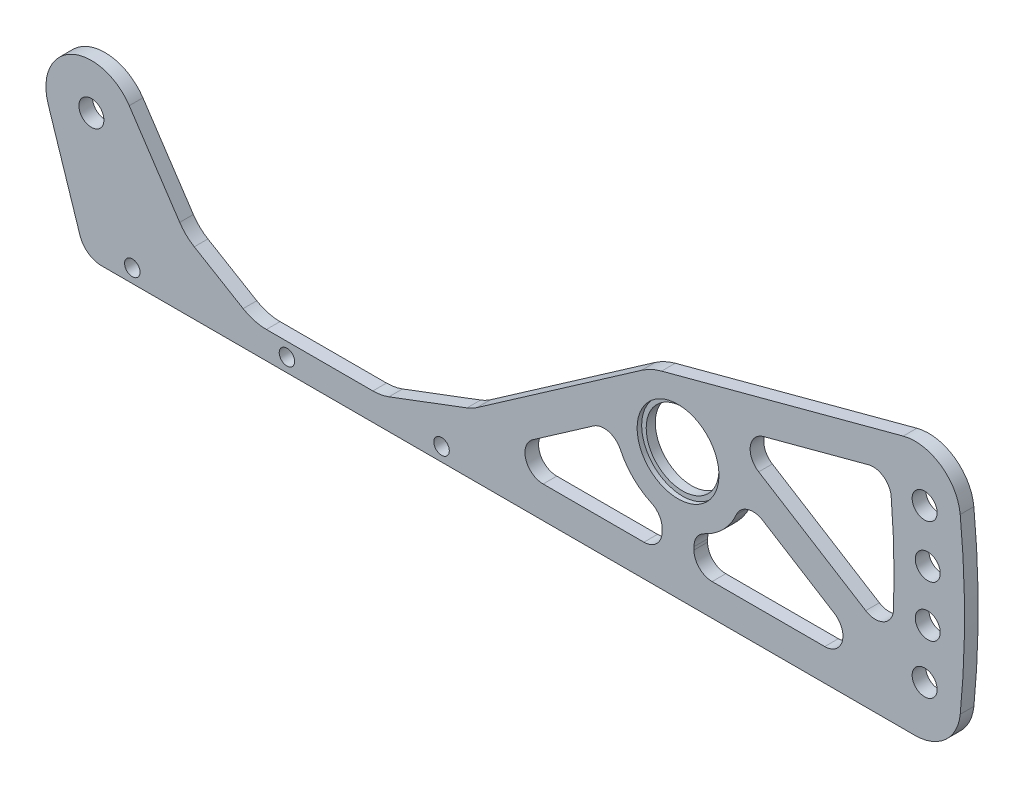
SolidWorks part; units mm, degrees
ref_plane "Спереди" through (0, 0, 0) normal (0, 0, 1) x (1, 0, 0)
ref_plane "Сверху" through (0, 0, 0) normal (0, 1, 0) x (1, 0, 0)
ref_plane "Справа" through (0, 0, 0) normal (1, 0, 0) x (0, 0, -1)
sketch "Эскиз1" plane through (0, 0, 0) normal (0, 0, 1) x (1, 0, 0)
  line L0 (-31.9542, -25) -> (253.1565, -25) construction
  line L1 (9, 35.6094) -> (9, -47.5785) construction
  line L2 (-39.2405, -28) -> (262.4545, -28) construction
  line L3 (-31.9542, -22) -> (262.4545, -22) construction
  line L4 (-9.5085, -3.0964) -> (-1.3987, -28)
  line L5 (8.3266, 5.5379) -> (20.6752, -13.0291)
  line L6 (-26.4187, 0) -> (187.6558, 0) construction
  line L7 (121.0002, 11.4893) -> (83.7656, -14.4365)
  line L8 (63.7181, -22) -> (35.7314, -22)
  line L9 (0, 0) -> (183.9142, 5.6191) construction
  line L10 (0, 0) -> (183.9142, -5.6191) construction
  line L11 (0, 0) -> (183.2281, -16.8363) construction
  line L12 (0, 0) -> (183.2281, 16.8363) construction
  line L13 (125.388, 13.526) -> (189.5368, 30.6561)
  line L14 (-1.3987, -28) -> (189.9474, -28)
  line L15 (43, -17.0585) -> (43, -35.954) construction
  line L16 (77, -17.0585) -> (77, -35.954) construction
  line L17 (20.6752, -13.0291) -> (35.7314, -22)
  line L18 (83.7656, -14.4365) -> (63.7181, -22)
  arc A0 (8.3266, 5.5379) -> (-9.5085, -3.0964) centre (0, 0) ccw
  circle A1 centre (129, 0) radius 8
  arc A2 (125.388, 13.526) -> (121.0002, 11.4893) centre (129, 0) ccw
  circle A3 centre (0, 0) radius 184 construction
  arc A4 (189.9474, -28) -> (189.5368, 30.6561) centre (0, 0) ccw
  dimension "D1" = 20
  dimension "D2" = 25
  dimension "D3" = 9
  dimension "D6" = 16
  dimension "D8" = 28
  dimension "D9" = 368
  dimension "D10" = 34
  dimension "D16" = 192
  dimension "D4" = 6
  dimension "D5" = 3
  dimension "D7" = 129
  dimension "D11" = 3.5
  dimension "D12" = 3.5
  dimension "D13" = 3.5
  dimension "D14" = 1.75
  dimension "D15" = 34
extrude "Бобышка-Вытянуть1" add sketch "Эскиз1" along normal blind 3
hole_wizard "Отверстие с зазором M31" positions "Эскиз3" profile "Эскиз2" hole size "M3" standard "Ansi Metric" end condition through all
sketch "Эскиз3" plane through (0, 0, 3) normal (0, 0, 1) x (1, 0, 0)
  line L0 (-31.9542, -25) -> (253.1565, -25) construction
  line L1 (9, 35.6094) -> (9, -47.5785) construction
  line L2 (43, -17.0585) -> (43, -35.954) construction
  line L3 (77, -17.0585) -> (77, -35.954) construction
  point P0 (9, -25)
  point P6 (43, -25)
  point P10 (77, -25)
sketch "Эскиз2" plane through (9, -25, 3) normal (1, 0, 0) x (0, -1, 0)
  line L0 (0, 0) -> (0, 3)
  line L1 (0, 3) -> (1.7, 3)
  line L2 (1.7, 3) -> (1.7, 0)
  line L5 (1.7, 0) -> (0, 0)
  line L11 (0, -6.35) -> (0, 107.95) construction
  dimension "Диаметр сквозного отверстия" = 3.4
  dimension "Глубина сквозного отверстия" = 3
hole_wizard "Отверстие с зазором M51" positions "Эскиз5" profile "Эскиз4" hole size "M5" standard "Ansi Metric" end condition through all
sketch "Эскиз5" plane through (0, 0, 3) normal (0, 0, 1) x (1, 0, 0)
  point P2 (0, 0)
sketch "Эскиз4" plane through (0, 0, 3) normal (1, 0, 0) x (0, -1, 0)
  line L0 (0, 0) -> (0, 3)
  line L1 (0, 3) -> (2.75, 3)
  line L2 (2.75, 3) -> (2.75, 0)
  line L5 (2.75, 0) -> (0, 0)
  line L11 (0, -6.35) -> (0, 107.95) construction
  dimension "Диаметр сквозного отверстия" = 5.5
  dimension "Глубина сквозного отверстия" = 3
hole_wizard "Отверстие с зазором M52" positions "Эскиз7" profile "Эскиз6" hole size "M5" standard "Ansi Metric" end condition through all
sketch "Эскиз7" plane through (0, 0, 3) normal (0, 0, 1) x (1, 0, 0)
  point P0 (183.2281, 16.8363)
  point P3 (183.9142, 5.6191)
  point P6 (183.9142, -5.6191)
  point P9 (183.2281, -16.8363)
sketch "Эскиз6" plane through (183.2281, 16.8363, 3) normal (1, 0, 0) x (0, -1, 0)
  line L0 (0, 0) -> (0, 3)
  line L1 (0, 3) -> (2.75, 3)
  line L2 (2.75, 3) -> (2.75, 0)
  line L5 (2.75, 0) -> (0, 0)
  line L11 (0, -6.35) -> (0, 107.95) construction
  dimension "Диаметр сквозного отверстия" = 5.5
  dimension "Глубина сквозного отверстия" = 3
fillet "Скругление1" radius 10 6 edges at (35.7314, -22, 1.5) (20.6752, -13.0291, 1.5) (63.7181, -22, 1.5) (83.7656, -14.4365, 1.5) (189.9474, -28, 1.5) (189.5368, 30.6561, 1.5)
fillet "Скругление2" radius 5 1 edges at (-1.3987, -28, 1.5)
sketch "Эскиз8" plane through (0, 0, 3) normal (0, 0, 1) x (1, 0, 0)
  line L0 (138.9079, 9.8911) -> (175.4042, 19.6369)
  line L1 (178.5224, 27.7149) -> (125.388, 13.526) construction
  line L2 (142.9717, -0.889) -> (175.2463, -21)
  line L3 (175.2463, -21) -> (132.5, -21)
  line L4 (2.2315, -28) -> (181.1077, -28) construction
  line L5 (115.0501, -1.1834) -> (86.5894, -21)
  line L6 (121.0002, 11.4893) -> (84.7863, -13.7258) construction
  line L8 (125.5, -13.5554) -> (125.5, -21)
  line L9 (132.5, -13.5554) -> (132.5, -21)
  line L10 (138.9079, 9.8911) -> (176.0039, -13.2243)
  line L11 (125.5, -21) -> (86.5894, -21)
  arc A0 (115.0501, -1.1834) -> (125.5, -13.5554) centre (129, 0) ccw
  arc A1 (125.388, 13.526) -> (121.0002, 11.4893) centre (129, 0) ccw construction
  arc A2 (176.0039, -13.2243) -> (175.4042, 19.6369) centre (0, 0) ccw
  arc A3 (132.5, -13.5554) -> (142.9717, -0.889) centre (129, 0) ccw
  dimension "D2" = 353
  dimension "D1" = 7
  dimension "D3" = 7
  dimension "D4" = 7
  dimension "D5" = 7
  dimension "D6" = 3.5
  dimension "D7" = 7
extrude "Вырез-Вытянуть1" cut sketch "Эскиз8" against normal through all
fillet "Скругление3" radius 4 11 edges at (86.5894, -21, 1.5) (125.5, -21, 1.5) (115.0501, -1.1834, 1.5) (125.5, -13.5554, 1.5) (132.5, -21, 1.5) (132.5, -13.5554, 1.5) (142.9717, -0.889, 1.5) (175.2463, -21, 1.5) (176.0039, -13.2243, 1.5) (175.4042, 19.6369, 1.5) (138.9079, 9.8911, 1.5)
sketch "Эскиз9" plane through (0, 0, 3) normal (0, 0, -1) x (-1, 0, 0)
  circle A0 centre (-129, 0) radius 9
  dimension "D1" = 18
extrude "Вырез-Вытянуть2" cut sketch "Эскиз9" along normal blind 1
equation "\"D12@Эскиз1\"=\"D11@Эскиз1\""
equation "\"D13@Эскиз1\"=\"D11@Эскиз1\""
equation "\"D14@Эскиз1\"=\"D11@Эскиз1\"/2"
